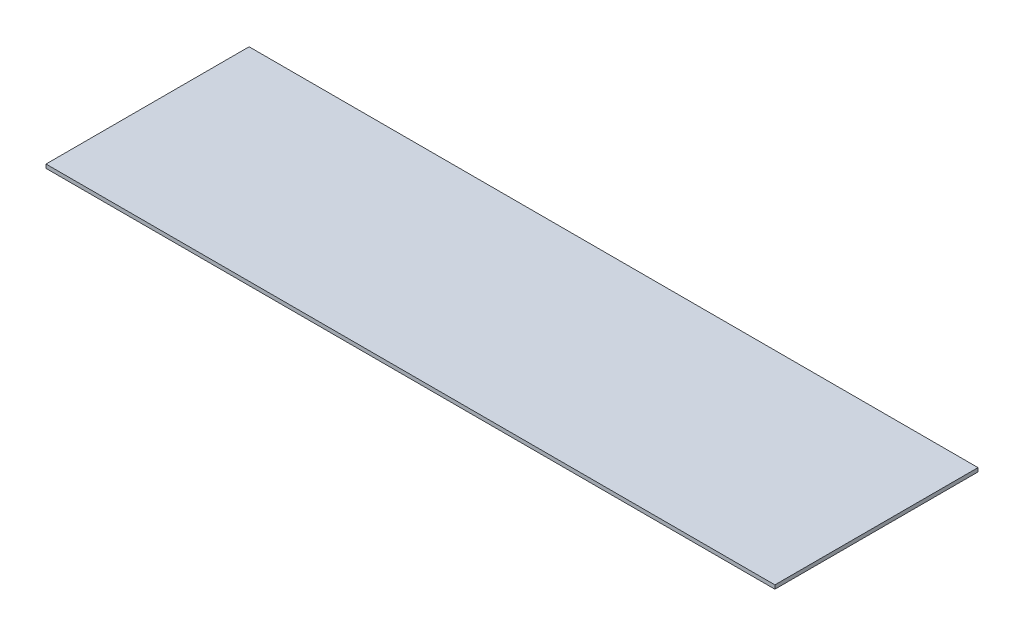
SolidWorks part; units mm, degrees
ref_plane "Front Plane" through (0, 0, 0) normal (0, 0, 1) x (1, 0, 0)
ref_plane "Top Plane" through (0, 0, 0) normal (0, 1, 0) x (1, 0, 0)
ref_plane "Right Plane" through (0, 0, 0) normal (1, 0, 0) x (0, 0, -1)
sketch "Sketch1" plane through (0, 0, 0) normal (0, 1, 0) x (1, 0, 0)
  line L1 (-1219.2, -339.725) -> (1219.2, -339.725)
  line L2 (-1219.2, -339.725) -> (-1219.2, 339.725)
  line L3 (-1219.2, 339.725) -> (1219.2, 339.725)
  line L4 (1219.2, -339.725) -> (1219.2, 339.725)
  line L5 (-1219.2, -339.725) -> (1219.2, 339.725) construction
  line L6 (-1219.2, 339.725) -> (1219.2, -339.725) construction
  point P0 (0, 0)
  dimension "D1" = 679.45
  dimension "D2" = 2438.4
extrude "Boss-Extrude1" add sketch "Sketch1" along normal blind 12.7
